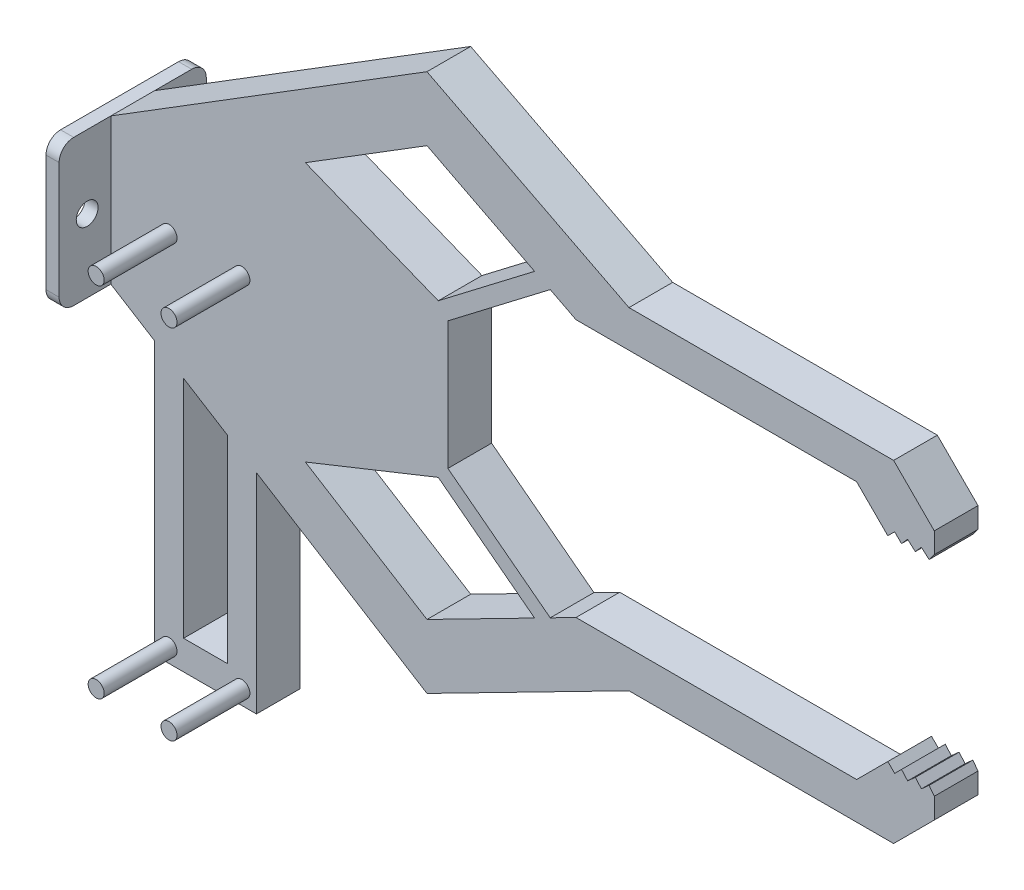
SolidWorks part; units mm, degrees
ref_plane "前视基准面" through (0, 0, 0) normal (0, 0, 1) x (1, 0, 0)
ref_plane "上视基准面" through (0, 0, 0) normal (0, 1, 0) x (1, 0, 0)
ref_plane "右视基准面" through (0, 0, 0) normal (1, 0, 0) x (0, 0, -1)
sketch "草图1" plane through (0, 0, 0) normal (0, 0, 1) x (1, 0, 0)
  line L0 (0, 0) -> (116, 0) construction
  line L1 (0, 10) -> (0, -10)
  line L2 (0, 10) -> (43.3919, 36.9535)
  line L3 (43.3919, 36.9535) -> (71.1157, 22.7729)
  line L4 (71.1157, 22.7729) -> (107.4399, 22.7729)
  line L5 (107.4399, 22.7729) -> (113.0229, 17.19)
  line L6 (113.0229, 17.19) -> (113.0229, 14.3598)
  line L7 (113.0229, 14.3598) -> (105.703, 14.3598)
  line L8 (105.703, 14.3598) -> (102.3649, 17.6979)
  line L9 (102.3649, 17.6979) -> (63.8448, 17.6979)
  line L10 (63.8448, 17.6979) -> (43.3919, 28.1595)
  line L11 (43.3919, 28.1595) -> (15.6501, 10.9273)
  line L12 (113.0229, -14.3598) -> (105.703, -14.3598)
  line L13 (0, -10) -> (43.3919, -36.9535)
  line L14 (105.703, -14.3598) -> (102.3649, -17.6979)
  line L15 (102.3649, -17.6979) -> (63.8448, -17.6979)
  line L16 (63.8448, -17.6979) -> (43.3919, -28.1595)
  line L17 (43.3919, -28.1595) -> (15.6501, -10.9273)
  line L18 (15.6501, 10.9273) -> (15.6501, -10.9273)
  line L20 (113.0229, -17.19) -> (113.0229, -14.3598)
  line L21 (107.4399, -22.7729) -> (113.0229, -17.19)
  line L22 (71.1157, -22.7729) -> (107.4399, -22.7729)
  line L23 (43.3919, -36.9535) -> (71.1157, -22.7729)
  dimension "D1" = 116
  dimension "D2" = 20
extrude "凸台-拉伸1" add sketch "草图1" along normal blind 6
sketch "草图2" plane through (0, 0, 6) normal (0, 0, 1) x (1, 0, 0)
  line L0 (15.6501, 0) -> (122.1197, 0) construction
  line L1 (15.6501, -10.9273) -> (15.6501, 10.9273) construction
  line L2 (105.703, 14.3598) -> (106.6435, 13.4193)
  line L3 (106.6435, 13.4193) -> (107.5841, 14.3598)
  line L4 (105.703, 14.3598) -> (113.0229, 14.3598) construction
  line L5 (107.5841, 14.3598) -> (108.5246, 13.4193)
  line L6 (108.5246, 13.4193) -> (109.3629, 14.3598)
  line L7 (109.3629, 14.3598) -> (110.4182, 13.4193)
  line L8 (110.4182, 13.4193) -> (111.2565, 14.3598)
  line L9 (111.2565, 14.3598) -> (112.3118, 13.4193)
  line L10 (112.3118, 13.4193) -> (113.0229, 14.3598)
  line L11 (113.0229, 14.3598) -> (105.703, 14.3598)
  line L12 (113.0229, -14.3598) -> (105.703, -14.3598)
  line L13 (112.3118, -13.4193) -> (113.0229, -14.3598)
  line L14 (111.2565, -14.3598) -> (112.3118, -13.4193)
  line L15 (110.4182, -13.4193) -> (111.2565, -14.3598)
  line L16 (109.3629, -14.3598) -> (110.4182, -13.4193)
  line L17 (108.5246, -13.4193) -> (109.3629, -14.3598)
  line L18 (107.5841, -14.3598) -> (108.5246, -13.4193)
  line L19 (106.6435, -13.4193) -> (107.5841, -14.3598)
  line L20 (105.703, -14.3598) -> (106.6435, -13.4193)
  point P27 (0, 0)
  line M8 (113.0229, -14.3598) -> (105.703, -14.3598)
  line M18 (105.703, 14.3598) -> (113.0229, 14.3598)
extrude "凸台-拉伸2" add sketch "草图2" against normal up to vertex (6 mm away) contours L9 L10 M18 | L7 L8 M18 | L5 L6 M18 | L2 L3 M18 | L20 L12 L19 | L18 L17 M8 | L16 L12 L15 | L14 L13 M8 up to point (113.0228, 14.3598, 0)
sketch "草图3" plane through (0, 0, 6) normal (0, 0, 1) x (1, 0, 0)
  line L0 (15.6501, 0) -> (52.6942, 0) construction
  line L1 (15.6501, -10.9273) -> (15.6501, 10.9273) construction
  line L2 (26.6964, 17.7889) -> (44.9405, 10.4973)
  line L3 (15.6501, 10.9273) -> (43.3919, 28.1595) construction
  line L4 (44.9405, 10.4973) -> (61.6408, 23.2611)
  line L5 (61.6408, 23.2611) -> (62.9608, 21.534)
  line L6 (62.9608, 21.534) -> (46.2605, 8.7702)
  line L7 (46.2605, 8.7702) -> (46.2605, -8.7702)
  line L8 (62.9608, -21.534) -> (46.2605, -8.7702)
  line L9 (61.6408, -23.2611) -> (62.9608, -21.534)
  line L10 (44.9405, -10.4973) -> (61.6408, -23.2611)
  line L11 (26.6964, -17.7889) -> (44.9405, -10.4973)
  line L12 (26.6964, 17.7889) -> (15.6501, 10.9273)
  line L13 (15.6501, 10.9273) -> (15.6501, -10.9273)
  line L14 (15.6501, -10.9273) -> (26.6964, -17.7889)
  point P14 (46.2605, 0)
extrude "凸台-拉伸3" add sketch "草图3" against normal up to vertex (6 mm away)
sketch "草图4" plane through (0, 0, 0) normal (-1, 0, 0) x (0, 0, 1)
  line L0 (3, 10) -> (3, -17.3627) construction
  line L1 (6, 10) -> (0, 10) construction
  line L2 (-7.1, 0) -> (30.3564, 0) construction
  line L3 (-5.1, -10) -> (11.1, -10)
  line L4 (-7.1, -8) -> (-7.1, 8)
  line L5 (-5.1, 10) -> (11.1, 10)
  line L6 (13.1, -8) -> (13.1, 8)
  arc A0 (13.1, -8) -> (11.1, -10) centre (11.1, -8) cw
  arc A1 (-5.1, -10) -> (-7.1, -8) centre (-5.1, -8) cw
  arc A2 (-5.1, 10) -> (-7.1, 8) centre (-5.1, 8) ccw
  arc A3 (11.1, 10) -> (13.1, 8) centre (11.1, 8) cw
  circle A4 centre (9.25, 0) radius 1.5
  circle A5 centre (-3.25, 0) radius 1.5
  point P14 (-7.1, 10)
  point P17 (13.1, 10)
  dimension "D2" = 2
  dimension "D3" = 12.5
  dimension "D4" = 3
  dimension "D1" = 20.2
extrude "凸台-拉伸4" add sketch "草图4" along normal blind 1.8
sketch "草图5" plane through (0, 0, 6) normal (0, 0, 1) x (1, 0, 0)
  line L0 (7.9847, 0) -> (17.9847, 0) construction
  line L1 (7.9847, 0) -> (7.9847, -49.1) construction
  circle A0 centre (17.9847, 0) radius 1.1
  circle A1 centre (7.9847, 0) radius 1.1
  circle A2 centre (7.9847, -49.1) radius 1.1
  circle A3 centre (17.9847, -49.1) radius 1.1
  dimension "D2" = 2.2
  dimension "D3" = 2.2
  dimension "D5" = 2.2
  dimension "D6" = 2.2
  dimension "D1" = 10
  dimension "D4" = 49.1
extrude "凸台-拉伸5" add sketch "草图5" along normal blind 10
sketch "草图6" plane through (0, 0, 6) normal (0, 0, -1) x (-1, 0, 0)
  line L0 (-17.9847, -49.1) -> (-7.9847, -49.1) construction
  line L1 (-7.9847, -49.1) -> (-7.9847, -8.3146) construction
  line L3 (-7.9847, -8.3146) -> (-17.9847, -8.3146) construction
  line L4 (-17.9847, -8.3146) -> (-17.9847, -49.1) construction
  line L5 (-19.9847, -8.3146) -> (-19.9847, -51.1)
  line L6 (-19.9847, -51.1) -> (-5.9847, -51.1)
  line L7 (-5.9847, -51.1) -> (-5.9847, -8.3146)
  line L8 (-15.9847, -8.3146) -> (-15.9847, -47.1)
  line L9 (-15.9847, -47.1) -> (-9.9847, -47.1)
  line L10 (-9.9847, -47.1) -> (-9.9847, -8.3146)
  line L11 (-19.9847, -8.3146) -> (-15.9847, -8.3146)
  line L12 (-9.9847, -8.3146) -> (-5.9847, -8.3146)
  point P16 (0, 0)
  dimension "D1" = 2
  dimension "D2" = 2
extrude "凸台-拉伸6" add sketch "草图6" along normal up to vertex
